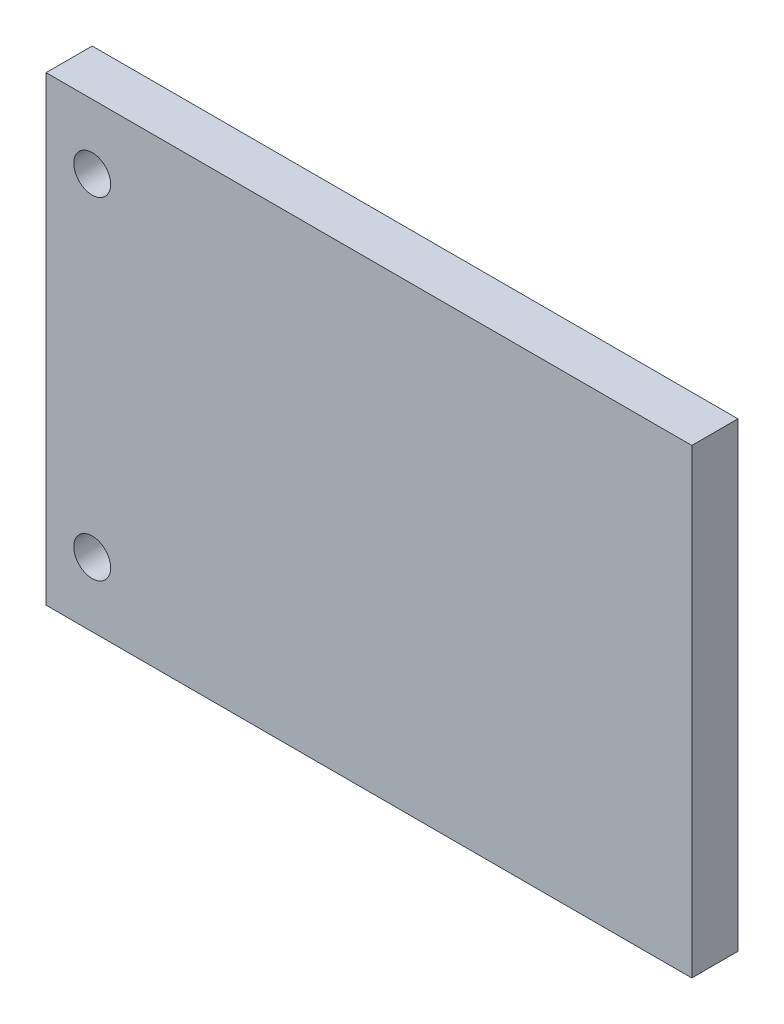
SolidWorks part; units mm, degrees
ref_plane "Plan de face" through (0, 0, 0) normal (0, 0, 1) x (1, 0, 0)
ref_plane "Plan de dessus" through (0, 0, 0) normal (0, 1, 0) x (1, 0, 0)
ref_plane "Plan de droite" through (0, 0, 0) normal (1, 0, 0) x (0, 0, -1)
sketch "Esquisse1" plane through (0, 0, 0) normal (0, 0, 1) x (1, 0, 0)
  line L0 (0, 0) -> (-19.7994, 0) construction
  line L1 (35, -25) -> (-35, -25)
  line L2 (35, -25) -> (35, 25)
  line L3 (35, 25) -> (-35, 25)
  line L4 (-35, -25) -> (-35, 25)
  line L5 (35, -25) -> (-35, 25) construction
  line L6 (35, 25) -> (-35, -25) construction
  circle A0 centre (-30, 18) radius 2
  circle A1 centre (-30, -18) radius 2
  point P0 (0, 0)
  dimension "D3" = 4
  dimension "D4" = 5
  dimension "D5" = 36
  dimension "D1" = 70
  dimension "D2" = 50
extrude "Boss.-Extru.1" add sketch "Esquisse1" along normal blind 5
